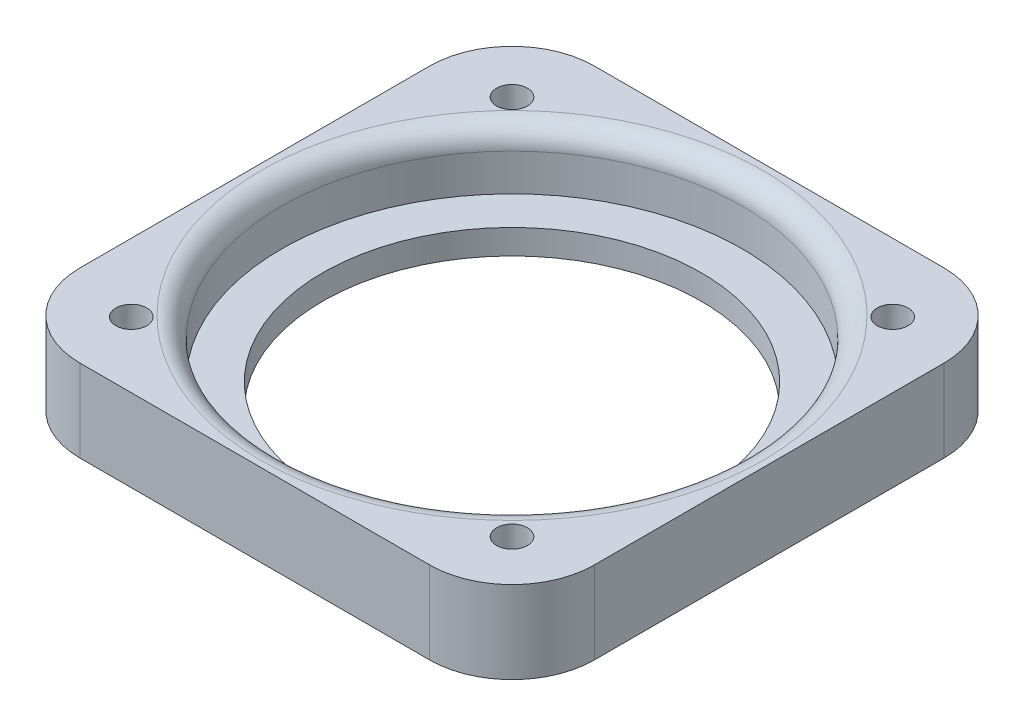
SolidWorks part; units mm, degrees
ref_plane "前视基准面" through (0, 0, 0) normal (0, 0, 1) x (1, 0, 0)
ref_plane "上视基准面" through (0, 0, 0) normal (0, 1, 0) x (1, 0, 0)
ref_plane "右视基准面" through (0, 0, 0) normal (1, 0, 0) x (0, 0, -1)
sketch "草图1" plane through (0, 0, 0) normal (0, 1, 0) x (1, 0, 0)
  circle A0 centre (0, 0) radius 25
extrude "凸台-拉伸1" add sketch "草图1" along normal blind 8
sketch "草图2" plane through (0, 8, 0) normal (0, 1, 0) x (1, 0, 0)
  circle A0 centre (0, 0) radius 22.4
  dimension "D1" = 44.8
extrude "切除-拉伸1" cut sketch "草图2" against normal blind 5.6
sketch "草图3" plane through (0, 2.4, 0) normal (0, 1, 0) x (1, 0, 0)
  circle A0 centre (0, 0) radius 18.4
  circle A1 centre (0, 0) radius 22.4 construction
  dimension "D1" = 4
extrude "切除-拉伸2" cut sketch "草图3" against normal blind 12.5
sketch "草图4" plane through (0, 0, 0) normal (0, 1, 0) x (1, 0, 0)
  line L1 (-25, 25) -> (25, 25)
  line L2 (-25, 25) -> (-25, -25)
  line L3 (-25, -25) -> (25, -25)
  line L4 (25, 25) -> (25, -25)
  line L5 (-25, 25) -> (25, -25) construction
  line L6 (-25, -25) -> (25, 25) construction
  circle A0 centre (0, 0) radius 25
  circle A1 centre (-18.3848, 18.3848) radius 1.5
  circle A2 centre (18.6152, 18.3848) radius 1.5
  circle A3 centre (18.6152, -18.6152) radius 1.5
  circle A4 centre (-18.3848, -18.6152) radius 1.5
  point P0 (0, 0)
  point P20 (0.1152, -0.1152)
  dimension "D3" = 3
  dimension "D4" = 26
  dimension "D6" = 37
  dimension "D7" = 37
  dimension "D1" = 50
  dimension "D2" = 50
  dimension "D5" = 4
extrude "凸台-拉伸2" add sketch "草图4" along normal blind 8 contours A0 L1 L2 | A0 L4 L1 | A0 L2 L3 | A0 L3 L4
fillet "圆角1" radius 8 4 edges at (-25, 4, 25) (25, 4, 25) (25, 4, -25) (-25, 4, -25)
sketch "草图5" plane through (0, 8, 0) normal (0, 1, 0) x (1, 0, 0)
  circle A0 centre (-18.3848, 18.3848) radius 1.5
  circle A1 centre (18.6152, 18.3848) radius 1.5
  circle A2 centre (18.6152, -18.6152) radius 1.5
  circle A3 centre (-18.3848, -18.6152) radius 1.5
  point P12 (0.1152, -0.1152)
  dimension "D1" = 4
extrude "切除-拉伸3" cut sketch "草图5" against normal blind 15
fillet "圆角2" radius 2 1 edges at (0, 8, 22.4)
sketch "草图6" plane through (0, 0, 0) normal (0, -1, 0) x (1, 0, 0)
  circle A0 centre (-18.3848, 18.6152) radius 3.5
  dimension "D1" = 7
extrude "切除-拉伸4" cut sketch "草图6" against normal blind 2
pattern_circular "阵列(圆周)1" count 4 over 360 about axis through (0, 0, 0) along (0, 1, 0) of "切除-拉伸4"
